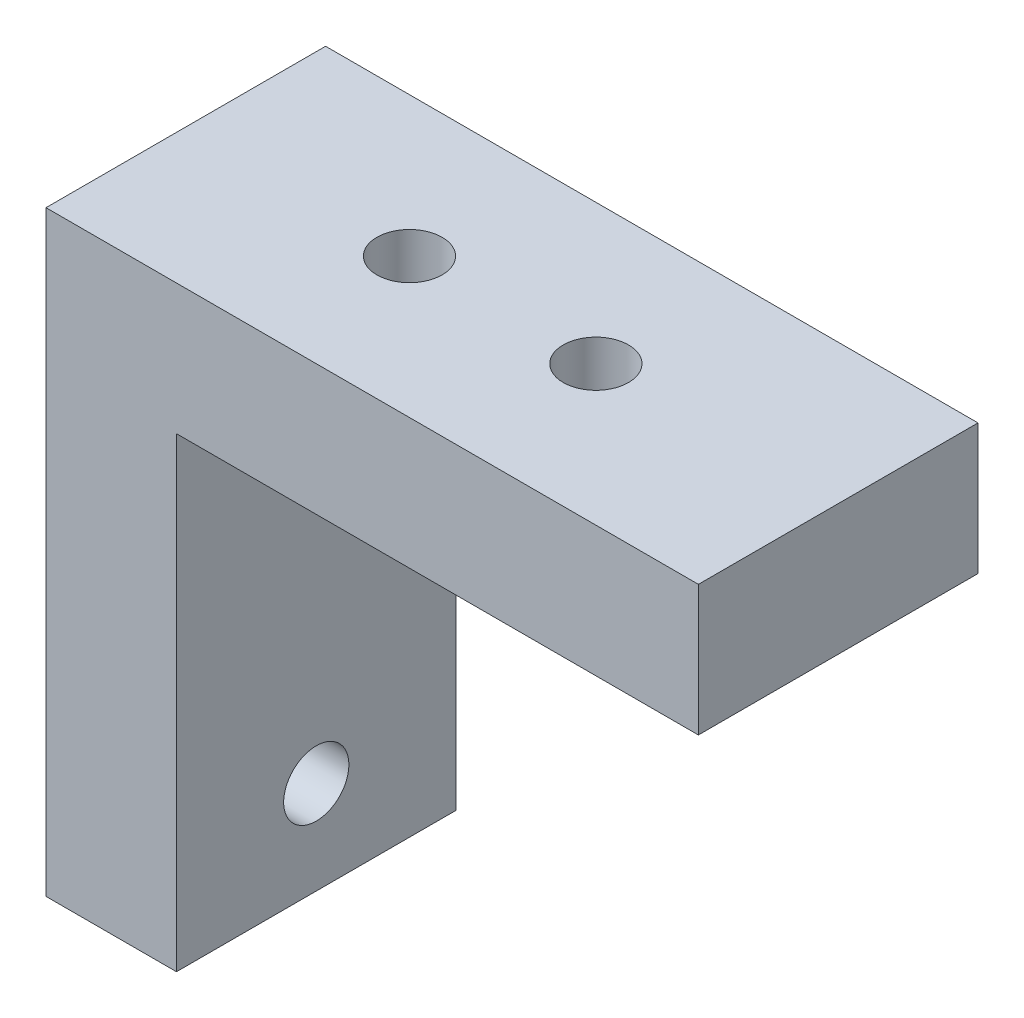
SolidWorks part; units mm, degrees
ref_plane "Front Plane" through (0, 0, 0) normal (0, 0, 1) x (1, 0, 0)
ref_plane "Top Plane" through (0, 0, 0) normal (0, 1, 0) x (1, 0, 0)
ref_plane "Right Plane" through (0, 0, 0) normal (1, 0, 0) x (0, 0, -1)
sketch "Sketch2" plane through (0, 0, 0) normal (1, 0, 0) x (0, 0, -1)
  line L1 (-4.6476, -15.7047) -> (10.3524, -15.7047)
  line L2 (-4.6476, -15.7047) -> (-4.6476, 9.2953)
  line L3 (-4.6476, 9.2953) -> (10.3524, 9.2953)
  line L4 (10.3524, -15.7047) -> (10.3524, 9.2953)
  dimension "D1" = 25
  dimension "D2" = 15
extrude "Boss-Extrude1" add sketch "Sketch2" along normal blind 7
sketch "Sketch3" plane through (7, 0, 0) normal (1, 0, 0) x (0, 0, -1)
  line L0 (2.8524, -10.7047) -> (2.8524, 4.2953) construction
  line L1 (2.8524, 4.2953) -> (2.8524, 9.2953) construction
  line L2 (10.3524, 9.2953) -> (-4.6476, 9.2953) construction
  circle A0 centre (2.8524, -10.7047) radius 1.75
  circle A1 centre (2.8524, 4.2953) radius 1.75
  dimension "D1" = 3.5
  dimension "D2" = 15
  dimension "D3" = 5
extrude "Cut-Extrude1" cut sketch "Sketch3" against normal through all
sketch "Sketch4" plane through (0, 9.2953, 0) normal (0, 1, 0) x (1, 0, 0)
  line L0 (7, 10.3524) -> (0, 10.3524) construction
  line L1 (0, -4.6476) -> (35, -4.6476)
  line L2 (0, -4.6476) -> (0, 10.3524)
  line L3 (0, 10.3524) -> (35, 10.3524)
  line L4 (35, -4.6476) -> (35, 10.3524)
  dimension "D1" = 35
extrude "Boss-Extrude2" add sketch "Sketch4" along normal blind 7
sketch "Sketch5" plane through (0, 16.2953, 0) normal (0, 1, 0) x (1, 0, 0)
  line L0 (12, 2.8524) -> (22, 2.8524) construction
  line L1 (22, 2.8524) -> (35, 2.8524) construction
  line L2 (35, -4.6476) -> (35, 10.3524) construction
  circle A0 centre (12, 2.8524) radius 1.75
  circle A1 centre (22, 2.8524) radius 1.75
  dimension "D1" = 3.5
  dimension "D2" = 10
  dimension "D3" = 5
extrude "Cut-Extrude2" cut sketch "Sketch5" against normal through all
